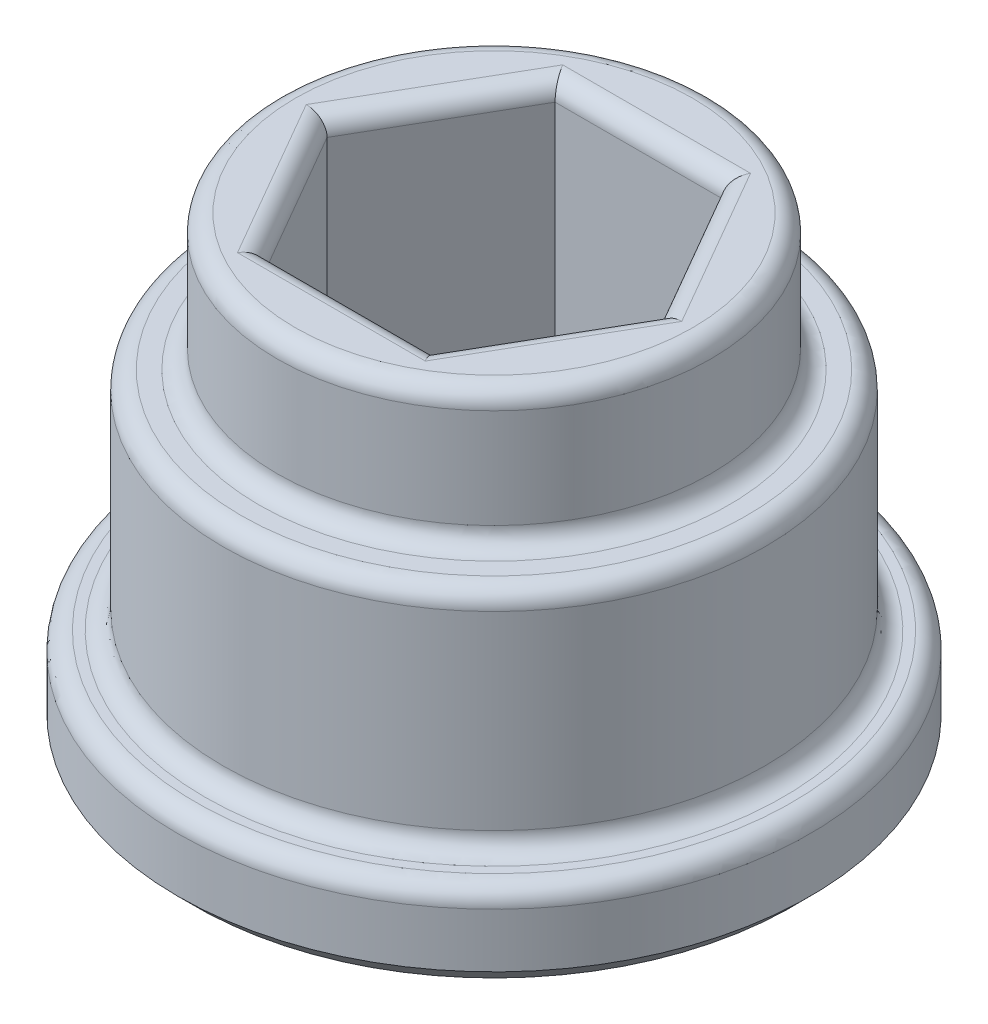
SolidWorks part; units mm, degrees
ref_plane "Front Plane" through (0, 0, 0) normal (0, 0, 1) x (1, 0, 0)
ref_plane "Top Plane" through (0, 0, 0) normal (0, 1, 0) x (1, 0, 0)
ref_plane "Right Plane" through (0, 0, 0) normal (1, 0, 0) x (0, 0, -1)
sketch "Sketch1" plane through (0, 0, 0) normal (0, 1, 0) x (1, 0, 0)
  line L1 (5.8659, 0) -> (2.9329, 5.08)
  line L2 (2.9329, 5.08) -> (-2.9329, 5.08)
  line L3 (-2.9329, 5.08) -> (-5.8659, 0)
  line L4 (-5.8659, 0) -> (-2.9329, -5.08)
  line L5 (-2.9329, -5.08) -> (2.9329, -5.08)
  line L6 (2.9329, -5.08) -> (5.8659, 0)
  circle A0 centre (0, 0) radius 5.08 construction
  circle A1 centre (0, 0) radius 9.525
  dimension "D2" = 19.05
  dimension "D1" = 10.16
extrude "Boss-Extrude1" add sketch "Sketch1" along normal blind 7.9375
sketch "Sketch2" plane through (0, 7.9375, 0) normal (0, 1, 0) x (1, 0, 0)
  line L0 (-2.9329, 5.08) -> (-5.8659, 0)
  line L1 (-5.8659, 0) -> (-2.9329, -5.08)
  line L2 (-2.9329, -5.08) -> (2.9329, -5.08)
  line L3 (2.9329, -5.08) -> (5.8659, 0)
  line L4 (5.8659, 0) -> (2.9329, 5.08)
  line L5 (2.9329, 5.08) -> (-2.9329, 5.08)
  circle A0 centre (0, 0) radius 7.62
  dimension "D1" = 15.24
extrude "Boss-Extrude2" add sketch "Sketch2" along normal blind 4.7625
sketch "Sketch3" plane through (0, 0, 0) normal (0, -1, 0) x (1, 0, 0)
  line L0 (-2.9329, 5.08) -> (2.9329, 5.08)
  line L2 (2.9329, 5.08) -> (5.8659, 0)
  line L3 (5.8659, 0) -> (2.9329, -5.08)
  line L4 (2.9329, -5.08) -> (-2.9329, -5.08)
  line L5 (-2.9329, -5.08) -> (-5.8659, 0)
  line L6 (-5.8659, 0) -> (-2.9329, 5.08)
  circle A0 centre (0, 0) radius 11.1125
  dimension "D1" = 22.225
extrude "Boss-Extrude3" add sketch "Sketch3" along normal blind 3.175 contours A0
fillet "Fillet1" radius 0.635 2 edges at (0, 0, 9.525) (0, 0, -11.1125)
fillet "Fillet3" radius 0.635 6 edges at (-4.3994, 12.7, 2.54) (0, 12.7, 5.08) (4.3994, 12.7, 2.54) (4.3994, 12.7, -2.54) (0, 12.7, -5.08) (-4.3994, 12.7, -2.54)
fillet "Fillet4" radius 0.635 3 edges at (0, 7.9375, 7.62) (0, 12.7, 7.62) (0, 7.9375, 9.525)
chamfer "Chamfer1" distance 0.635 angle 45 7 edges at (4.3994, -3.175, -2.54) (4.3994, -3.175, 2.54) (0, -3.175, 5.08) (-4.3994, -3.175, 2.54) (-4.3994, -3.175, -2.54) (0, -3.175, -5.08) (0, -3.175, -11.1125)
